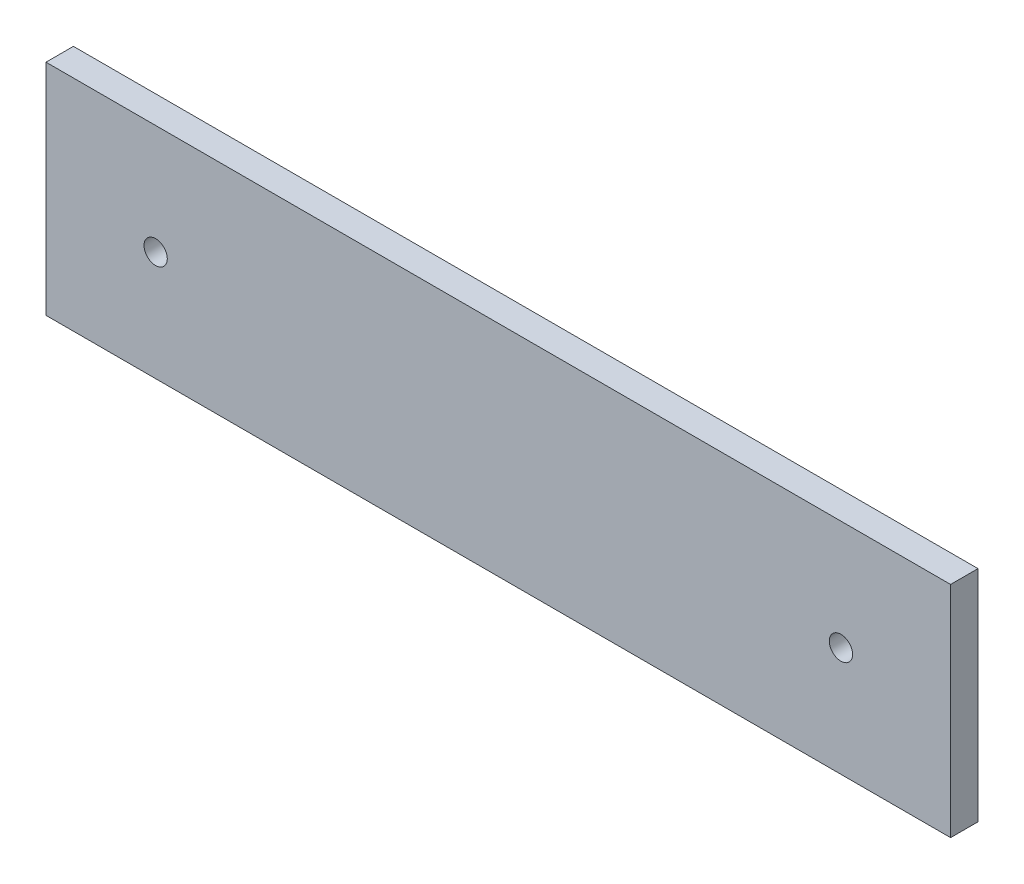
SolidWorks part; units mm, degrees
ref_plane "前视基准面" through (0, 0, 0) normal (0, 0, 1) x (1, 0, 0)
ref_plane "上视基准面" through (0, 0, 0) normal (0, 1, 0) x (1, 0, 0)
ref_plane "右视基准面" through (0, 0, 0) normal (1, 0, 0) x (0, 0, -1)
other "Configuration Table"
sketch "草图1" plane through (0, 0, 0) normal (0, 0, 1) x (1, 0, 0)
  line L1 (-16, -16) -> (116, -16)
  line L2 (-16, -16) -> (-16, 16)
  line L3 (-16, 16) -> (116, 16)
  line L4 (116, -16) -> (116, 16)
  line L5 (-16, -16) -> (116, 16) construction
  line L6 (-16, 16) -> (116, -16) construction
  circle A0 centre (0, 0) radius 1.7
  circle A1 centre (100, 0) radius 1.7
extrude "凸台-拉伸1" add sketch "草图1" along normal mid plane 4
